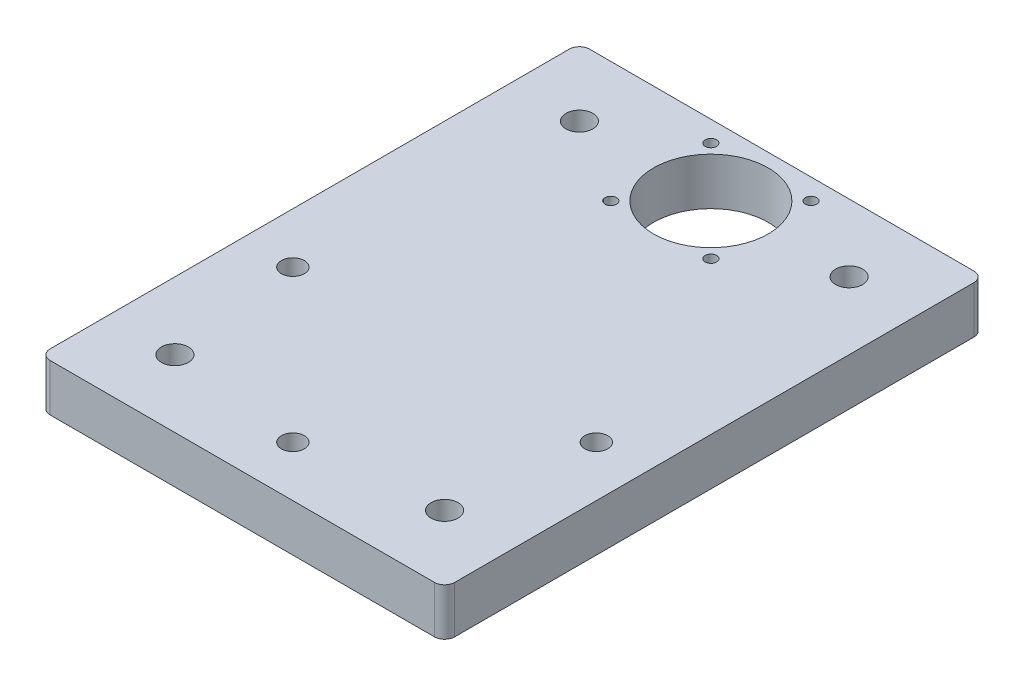
SolidWorks part; units mm, degrees
ref_plane "前视基准面" through (0, 0, 0) normal (0, 0, 1) x (1, 0, 0)
ref_plane "上视基准面" through (0, 0, 0) normal (0, 1, 0) x (1, 0, 0)
ref_plane "右视基准面" through (0, 0, 0) normal (1, 0, 0) x (0, 0, -1)
other "Configuration Table"
sketch "草图1" plane through (0, 0, 0) normal (0, 1, 0) x (1, 0, 0)
  line L0 (0, 60) -> (0, -100) construction
  line L1 (-57, -100) -> (57, -100)
  line L2 (-60, -97) -> (-60, 57)
  line L3 (-57, 60) -> (57, 60)
  line L4 (60, -97) -> (60, 57)
  line L5 (-60, -100) -> (60, 60) construction
  line L6 (-60, 60) -> (60, -100) construction
  line L7 (60, -20) -> (-60, -20) construction
  arc A0 (-57, -100) -> (-60, -97) centre (-57, -97) cw
  arc A1 (57, -100) -> (60, -97) centre (57, -97) ccw
  arc A2 (57, 60) -> (60, 57) centre (57, 57) cw
  arc A3 (-60, 57) -> (-57, 60) centre (-57, 57) cw
  dimension "D3" = 3
  dimension "D1" = 120
  dimension "D2" = 160
extrude "凸台-拉伸1" add sketch "草图1" along normal blind 14
sketch "草图3" plane through (0, 0, 0) normal (0, -1, 0) x (1, 0, 0)
  line L1 (57, -60) -> (-57, -60) construction
  line L2 (60, 97) -> (60, -57) construction
  circle A0 centre (14.8492, -24.1508) radius 1.7
  circle A1 centre (14.8492, -53.8492) radius 1.7
  circle A2 centre (-14.8492, -53.8492) radius 1.7
  circle A3 centre (-14.8492, -24.1508) radius 1.7
  dimension "D1" = 3.4
  dimension "D2" = 3.4
  dimension "D3" = 3.4
  dimension "D4" = 3.4
  dimension "D5" = 29.6985
  dimension "D6" = 29.6985
  dimension "D7" = 29.6985
  dimension "D8" = 29.6985
  dimension "D9" = 6.1508
  dimension "D10" = 45.1508
  dimension "D11" = 6.1508
  dimension "D12" = 45.1508
extrude "切除-拉伸1" cut sketch "草图3" against normal through all
cosmetic thread "装饰螺纹线4" parameters "D2"=4.4
cosmetic thread "装饰螺纹线5" parameters "D2"=4.4
cosmetic thread "装饰螺纹线6" parameters "D2"=4.4
cosmetic thread "装饰螺纹线7" parameters "D2"=4.4
sketch "草图4" plane through (0, 0, 0) normal (0, -1, 0) x (1, 0, 0)
  line L0 (-57, 100) -> (57, 100) construction
  line L3 (60, 97) -> (60, -57) construction
  line L6 (-60, -57) -> (-60, 97) construction
  circle A0 centre (0, 85) radius 3.4
  circle A1 centre (45, 40) radius 3.4
  circle A2 centre (-45, 40) radius 3.4
  dimension "D1" = 6.8
  dimension "D2" = 6.8
  dimension "D3" = 6.8
  dimension "D4" = 15
  dimension "D5" = 15
  dimension "D6" = 15
extrude "切除-拉伸2" cut sketch "草图4" against normal through all
cosmetic thread "装饰螺纹线1" parameters "D2"=7.8
cosmetic thread "装饰螺纹线2" parameters "D2"=7.8
cosmetic thread "装饰螺纹线3" parameters "D2"=7.8
sketch "草图5" plane through (0, 14, 0) normal (0, 1, 0) x (1, 0, 0)
  circle A0 centre (0, 39) radius 17
  dimension "D1" = 34
extrude "切除-拉伸3" cut sketch "草图5" against normal through all
sketch "草图6" plane through (0, 0, 0) normal (0, -1, 0) x (1, 0, 0)
  line L0 (0, 100) -> (0, -60) construction
  line L1 (-57, 100) -> (57, 100) construction
  line L2 (57, -60) -> (-57, -60) construction
  line L3 (60, 20) -> (-60, 20) construction
  line L4 (60, 97) -> (60, -57) construction
  line L5 (-60, -57) -> (-60, 97) construction
  circle A0 centre (40, 80) radius 4
  circle A1 centre (-40, 80) radius 4
  circle A2 centre (40, -40) radius 4
  circle A3 centre (-40, -40) radius 4
  dimension "D1" = 8
  dimension "D2" = 20
  dimension "D3" = 20
extrude "切除-拉伸4" cut sketch "草图6" against normal through all
